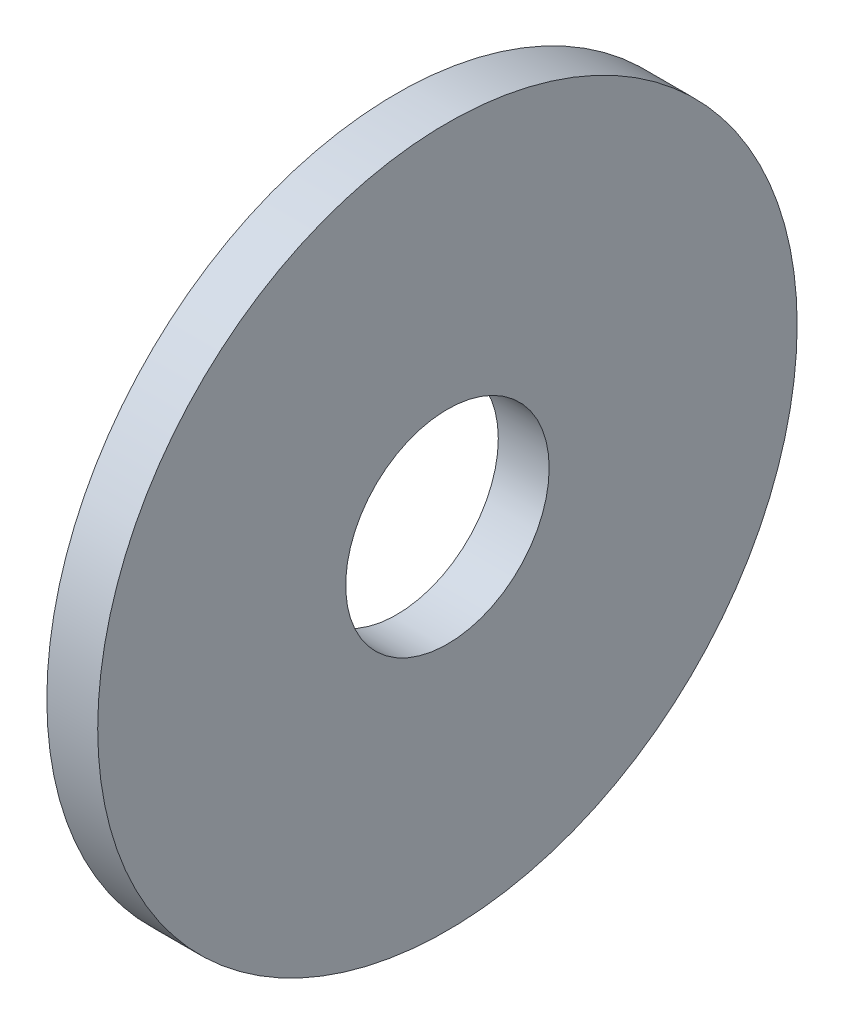
SolidWorks part; units mm, degrees
ref_plane "Plane1" through (0, 0, 0) normal (0, 0, 1) x (1, 0, 0)
ref_plane "Plane2" through (0, 0, 0) normal (0, 1, 0) x (1, 0, 0)
ref_plane "Plane3" through (0, 0, 0) normal (1, 0, 0) x (0, 0, -1)
sketch "Sketch1" plane through (0, 0, 0) normal (1, 0, 0) x (0, 0, -1)
  circle A0 centre (0, 0) radius 1.6
  circle A1 centre (0, 0) radius 5.5
  dimension "Insid_dia" = 3.2
  dimension "OutsideDia" = 11
extrude "Base-Extrude" add sketch "Sketch1" along normal blind 0.8
